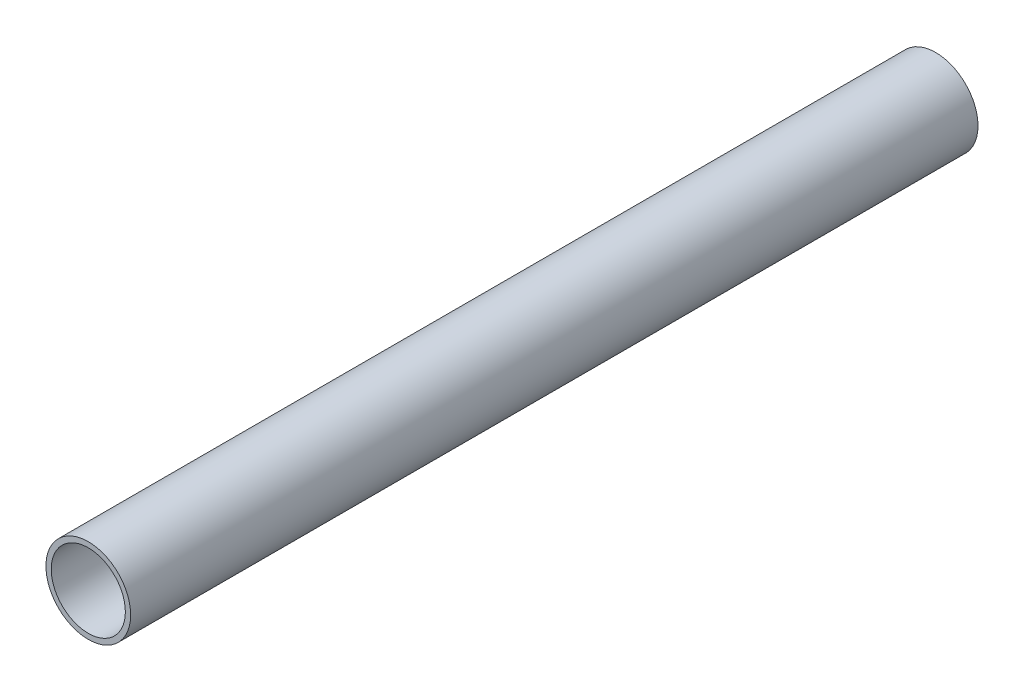
SolidWorks part; units mm, degrees
material "6061-T6 (SS)"
ref_plane "Front Plane" through (0, 0, 0) normal (0, 0, 1) x (1, 0, 0)
ref_plane "Top Plane" through (0, 0, 0) normal (0, 1, 0) x (1, 0, 0)
ref_plane "Right Plane" through (0, 0, 0) normal (1, 0, 0) x (0, 0, -1)
sketch "Sketch2" plane through (0, 0, 0) normal (0, 0, 1) x (1, 0, 0)
  circle A0 centre (0, 0) radius 11.1125
  circle A1 centre (0, 0) radius 12.7
  dimension "D1" = 25.4
  dimension "D2" = 1.5875
extrude "Boss-Extrude1" add sketch "Sketch2" along normal mid plane 254
sketch "Sketch3" plane through (0, 0, 0) normal (0, 1, 0) x (1, 0, 0)
  circle A0 centre (0, 0) radius 2.1526
  dimension "D1" = 4.3053
extrude "Cut-Extrude1" cut sketch "Sketch3" against normal through all
